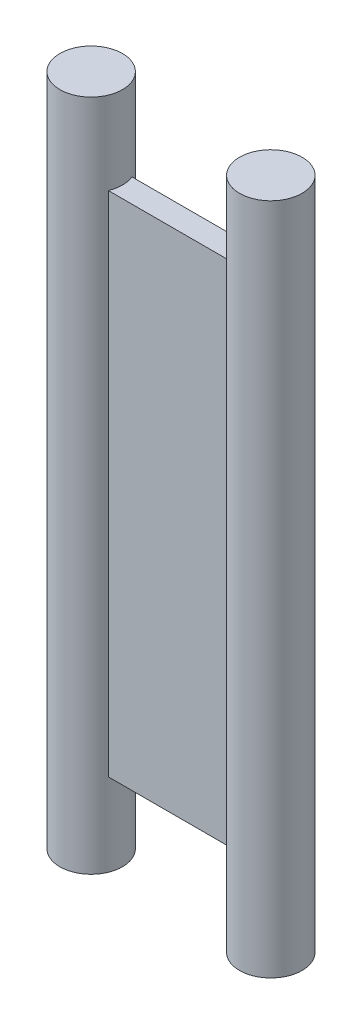
SolidWorks part; units mm, degrees
ref_plane "Front Plane" through (0, 0, 0) normal (0, 0, 1) x (1, 0, 0)
ref_plane "Top Plane" through (0, 0, 0) normal (0, 1, 0) x (1, 0, 0)
ref_plane "Right Plane" through (0, 0, 0) normal (1, 0, 0) x (0, 0, -1)
sketch "Sketch1" plane through (0, 0, 0) normal (0, 1, 0) x (1, 0, 0)
  line L1 (3.803, 0.5) -> (-3.803, 0.5)
  line L2 (3.803, 0.5) -> (3.803, -0.5)
  line L3 (3.803, -0.5) -> (-3.803, -0.5)
  line L4 (-3.803, 0.5) -> (-3.803, -0.5)
  line L5 (3.803, 0.5) -> (-3.803, -0.5) construction
  line L6 (3.803, -0.5) -> (-3.803, 0.5) construction
  point P0 (0, 0)
  dimension "D1" = 7.606
  dimension "D3" = 1
extrude "Boss-Extrude1" add sketch "Sketch1" along normal blind 21.5
ref_plane "Plane1" through (0, 10.75, 0) normal (0, 1, 0) x (1, 0, 0)
sketch "Sketch2" plane through (0, 10.75, 0) normal (0, 1, 0) x (1, 0, 0)
  line L0 (3.803, -0.5) -> (3.803, 0.5) construction
  line L1 (-3.803, 0.5) -> (-3.803, -0.5) construction
  line L2 (3.803, -0.5) -> (3.803, 0.5) construction
  line L3 (-3.803, 0.5) -> (-3.803, -0.5) construction
  circle A0 centre (-3.803, 0) radius 1.325
  circle A1 centre (3.803, 0) radius 1.325
  dimension "D1" = 2.65
extrude "Boss-Extrude2" add sketch "Sketch2" along normal mid plane 28.5
